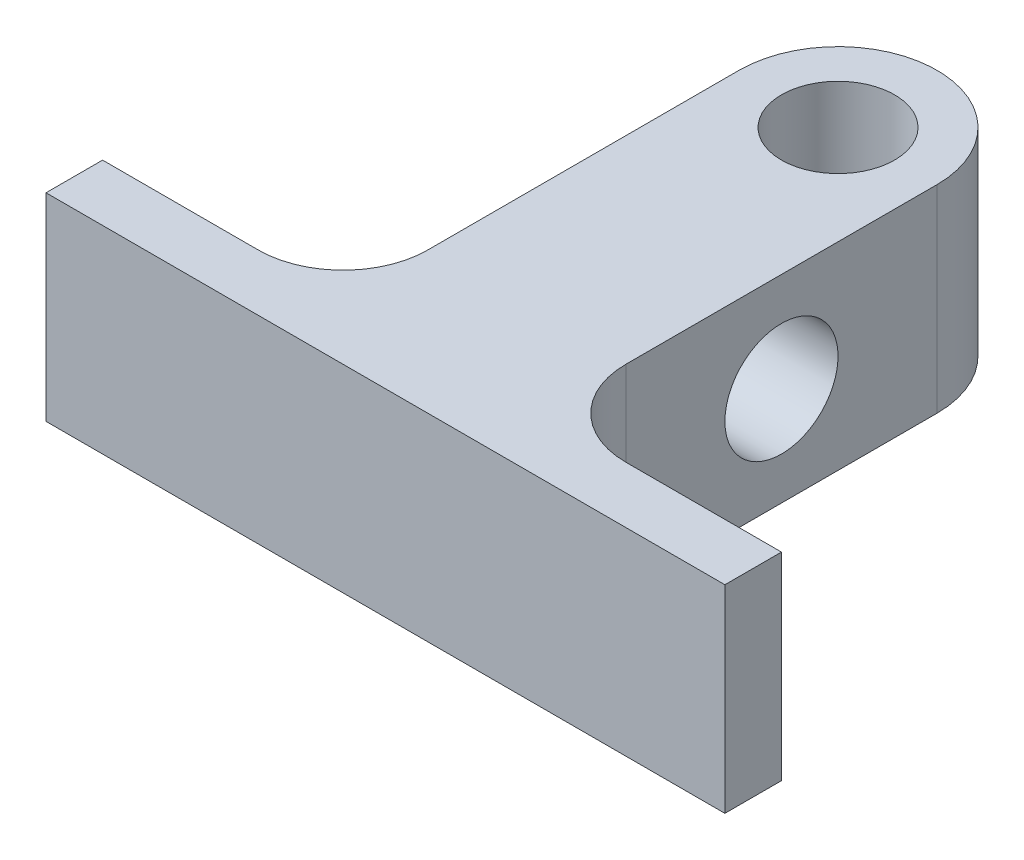
SolidWorks part; units mm, degrees
ref_plane "Front Plane" through (0, 0, 0) normal (0, 0, 1) x (1, 0, 0)
ref_plane "Top Plane" through (0, 0, 0) normal (0, 1, 0) x (1, 0, 0)
ref_plane "Right Plane" through (0, 0, 0) normal (1, 0, 0) x (0, 0, -1)
sketch "Sketch2" plane through (0, 0, 0) normal (0, 1, 0) x (1, 0, 0)
  line L0 (-8.75, -7.5) -> (-8.75, 20)
  line L1 (8.75, 20) -> (8.75, -7.5)
  line L2 (16.25, -15) -> (30, -15)
  line L3 (30, -15) -> (30, -20)
  line L4 (30, -20) -> (-30, -20)
  line L5 (-30, -20) -> (-30, -15)
  line L6 (-30, -15) -> (-16.25, -15)
  line L7 (0, -20) -> (0, 20) construction
  arc A0 (-8.75, 20) -> (8.75, 20) centre (0, 20) cw
  arc A1 (8.75, -7.5) -> (16.25, -15) centre (16.25, -7.5) ccw
  arc A2 (-16.25, -15) -> (-8.75, -7.5) centre (-16.25, -7.5) ccw
  circle A3 centre (0, 20) radius 5
  dimension "D1" = 10
  dimension "D2" = 17.5
  dimension "D7" = 7.5
  dimension "D3" = 20
  dimension "D4" = 20
  dimension "D5" = 5
  dimension "D6" = 30
extrude "Boss-Extrude1" add sketch "Sketch2" along normal blind 17.5
sketch "Sketch3" plane through (-8.75, 0, 0) normal (-1, 0, 0) x (0, 0, 1)
  line L0 (-6.25, 17.5) -> (-6.25, 0) construction
  line L1 (-20, 17.5) -> (7.5, 17.5) construction
  line L2 (-20, 0) -> (7.5, 0) construction
  line L4 (-20, 8.75) -> (7.5, 8.75) construction
  line L5 (-20, 17.5) -> (-20, 0) construction
  line L6 (7.5, 17.5) -> (7.5, 0) construction
  circle A0 centre (-6.25, 8.75) radius 5
  dimension "D1" = 10
extrude "Cut-Extrude1" cut sketch "Sketch3" against normal through all
